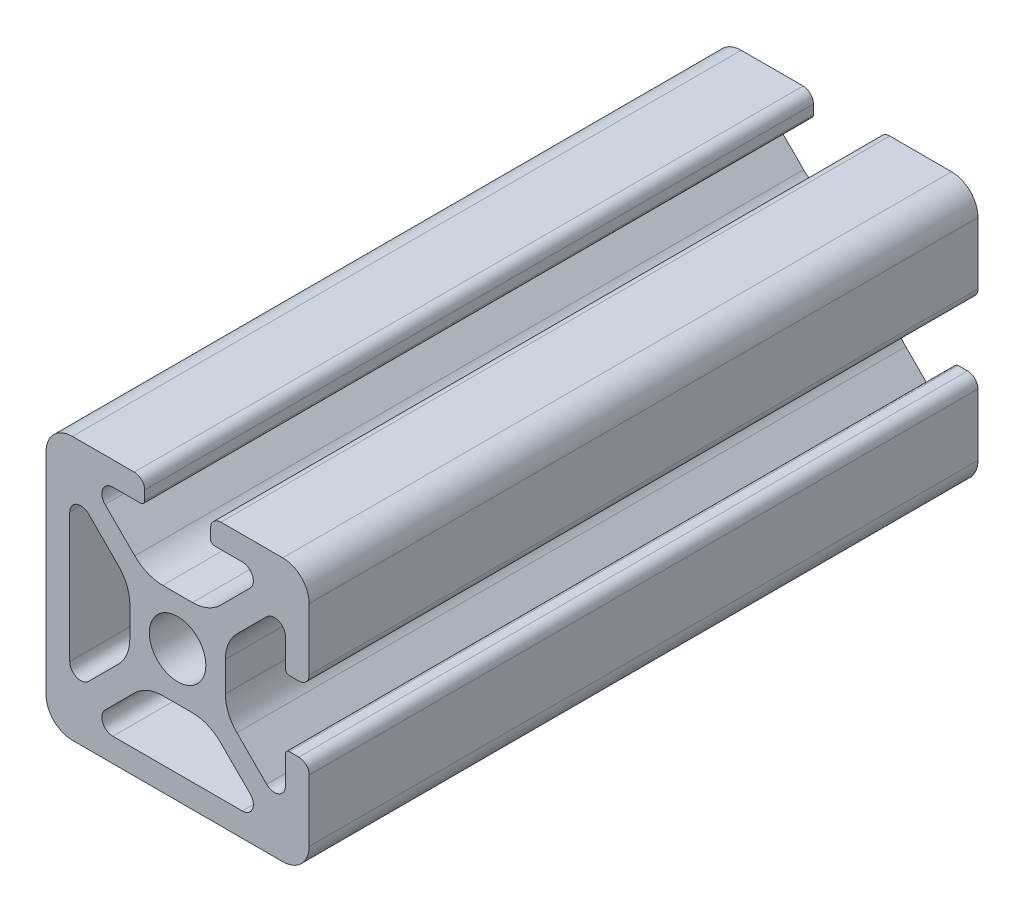
SolidWorks part; units mm, degrees
material "6061-T6 (SS)"
ref_plane "Front Plane" through (0, 0, 0) normal (0, 0, 1) x (1, 0, 0)
ref_plane "Top Plane" through (0, 0, 0) normal (0, 1, 0) x (1, 0, 0)
ref_plane "Right Plane" through (0, 0, 0) normal (1, 0, 0) x (0, 0, -1)
sketch "Sketch1" plane through (0, 0, 0) normal (0, 0, 1) x (1, 0, 0)
  line L2 (-9.9949, 7.9883) -> (-9.9949, -7.9883)
  line L3 (-7.9883, 9.9949) -> (-3.2893, 9.9949)
  line L4 (-2.5019, 9.2075) -> (-2.5019, 8.4963)
  line L5 (-2.8067, 8.1915) -> (-4.9149, 8.1915)
  line L6 (-5.5076, 6.7606) -> (-3.2528, 4.5058)
  line L7 (-6.7606, 5.5076) -> (-4.5058, 3.2528)
  line L8 (-8.1915, 4.9149) -> (-8.1915, -4.9149)
  line L11 (-1.1334, 3.6279) -> (1.1334, 3.6279)
  line L12 (-3.6279, 1.1334) -> (-3.6279, -1.1334)
  line L13 (8.4963, 2.5019) -> (9.2075, 2.5019)
  line L14 (8.1915, 4.9149) -> (8.1915, 2.8067)
  line L15 (9.9949, 7.9883) -> (9.9949, 3.2893)
  line L16 (7.9883, 9.9949) -> (3.2893, 9.9949)
  line L17 (2.5019, 9.2075) -> (2.5019, 8.4963)
  line L18 (2.8067, 8.1915) -> (4.9149, 8.1915)
  line L19 (3.6279, 1.1334) -> (3.6279, -1.1334)
  line L20 (5.5076, 6.7606) -> (3.2528, 4.5058)
  line L21 (6.7606, 5.5076) -> (4.5058, 3.2528)
  line L24 (-6.7606, -5.5076) -> (-4.5058, -3.2528)
  line L25 (-5.5076, -6.7606) -> (-3.2528, -4.5058)
  line L26 (4.9149, -8.1915) -> (-4.9149, -8.1915)
  line L28 (-7.9883, -9.9949) -> (7.9883, -9.9949)
  line L30 (9.9949, -7.9883) -> (9.9949, -3.2893)
  line L34 (5.5076, -6.7606) -> (3.2528, -4.5058)
  line L35 (6.7606, -5.5076) -> (4.5058, -3.2528)
  line L36 (8.1915, -4.9149) -> (8.1915, -2.8067)
  line L37 (8.4963, -2.5019) -> (9.2075, -2.5019)
  line L38 (-1.1334, -3.6279) -> (1.1334, -3.6279)
  circle A0 centre (0, 0) radius 2.1463
  arc A1 (-9.9949, 7.9883) -> (-7.9883, 9.9949) centre (-7.9883, 7.9883) cw
  arc A2 (-6.7606, 5.5076) -> (-8.1915, 4.9149) centre (-7.3533, 4.9149) ccw
  arc A3 (-4.9149, 8.1915) -> (-5.5076, 6.7606) centre (-4.9149, 7.3533) ccw
  arc A4 (-3.2893, 9.9949) -> (-2.5019, 9.2075) centre (-3.2893, 9.2075) cw
  arc A7 (-2.5019, 8.4963) -> (-2.8067, 8.1915) centre (-2.8067, 8.4963) cw
  arc A8 (-1.1334, 3.6279) -> (-3.2528, 4.5058) centre (-1.1334, 6.6251) cw
  arc A9 (-3.6279, 1.1334) -> (-4.5058, 3.2528) centre (-6.6251, 1.1334) ccw
  arc A10 (8.1915, 2.8067) -> (8.4963, 2.5019) centre (8.4963, 2.8067) ccw
  arc A11 (9.9949, 3.2893) -> (9.2075, 2.5019) centre (9.2075, 3.2893) cw
  arc A12 (9.9949, 7.9883) -> (7.9883, 9.9949) centre (7.9883, 7.9883) ccw
  arc A13 (3.2893, 9.9949) -> (2.5019, 9.2075) centre (3.2893, 9.2075) ccw
  arc A14 (2.5019, 8.4963) -> (2.8067, 8.1915) centre (2.8067, 8.4963) ccw
  arc A15 (1.1334, 3.6279) -> (3.2528, 4.5058) centre (1.1334, 6.6251) ccw
  arc A16 (3.6279, 1.1334) -> (4.5058, 3.2528) centre (6.6251, 1.1334) cw
  arc A17 (6.7606, 5.5076) -> (8.1915, 4.9149) centre (7.3533, 4.9149) cw
  arc A18 (4.9149, 8.1915) -> (5.5076, 6.7606) centre (4.9149, 7.3533) cw
  arc A19 (-3.6279, -1.1334) -> (-4.5058, -3.2528) centre (-6.6251, -1.1334) cw
  arc A20 (-1.1334, -3.6279) -> (-3.2528, -4.5058) centre (-1.1334, -6.6251) ccw
  arc A25 (-4.9149, -8.1915) -> (-5.5076, -6.7606) centre (-4.9149, -7.3533) cw
  arc A26 (-6.7606, -5.5076) -> (-8.1915, -4.9149) centre (-7.3533, -4.9149) cw
  arc A27 (-9.9949, -7.9883) -> (-7.9883, -9.9949) centre (-7.9883, -7.9883) ccw
  arc A28 (9.9949, -7.9883) -> (7.9883, -9.9949) centre (7.9883, -7.9883) cw
  arc A29 (6.7606, -5.5076) -> (8.1915, -4.9149) centre (7.3533, -4.9149) ccw
  arc A30 (4.9149, -8.1915) -> (5.5076, -6.7606) centre (4.9149, -7.3533) ccw
  arc A32 (9.9949, -3.2893) -> (9.2075, -2.5019) centre (9.2075, -3.2893) ccw
  arc A33 (8.1915, -2.8067) -> (8.4963, -2.5019) centre (8.4963, -2.8067) cw
  arc A35 (1.1334, -3.6279) -> (3.2528, -4.5058) centre (1.1334, -6.6251) cw
  arc A36 (3.6279, -1.1334) -> (4.5058, -3.2528) centre (6.6251, -1.1334) ccw
extrude "Boss-Extrude1" add sketch "Sketch1" along normal mid plane 50.8
